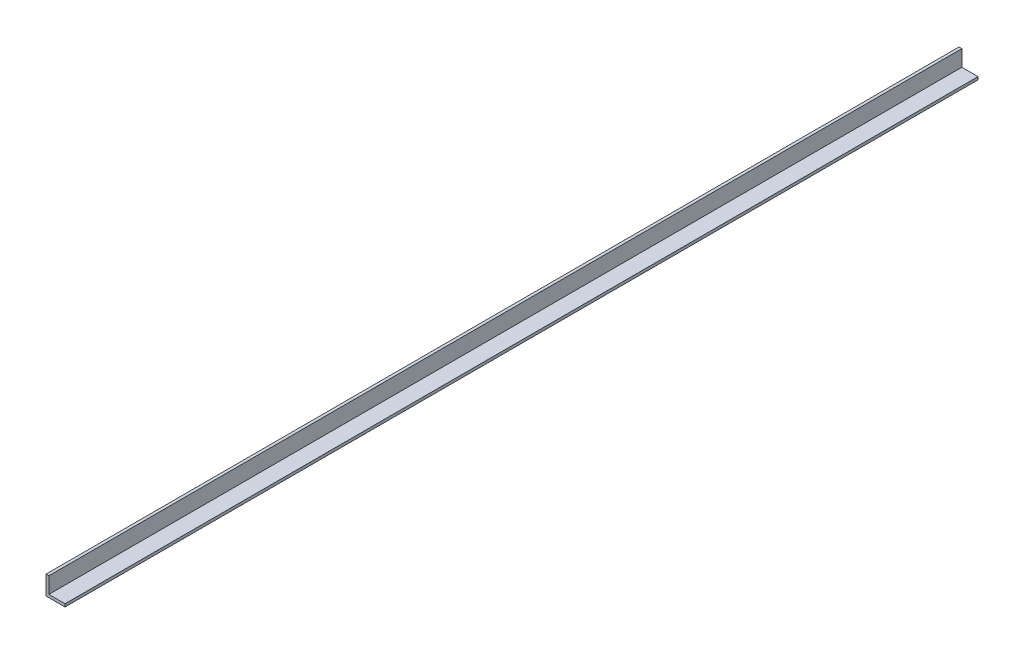
SolidWorks part; units mm, degrees
material "ASTM A36 Acero"
ref_plane "Alzado" through (0, 0, 0) normal (0, 0, 1) x (1, 0, 0)
ref_plane "Planta" through (0, 0, 0) normal (0, 1, 0) x (1, 0, 0)
ref_plane "Vista lateral" through (0, 0, 0) normal (1, 0, 0) x (0, 0, -1)
sketch "Croquis1" plane through (0, 0, 0) normal (0, 0, 1) x (1, 0, 0)
  line L0 (0, 127) -> (0, 0)
  line L1 (0, 0) -> (127, 0)
  line L2 (127, 0) -> (127, 19.05)
  line L3 (127, 19.05) -> (19.05, 19.05)
  line L4 (19.05, 19.05) -> (19.05, 127)
  line L5 (19.05, 127) -> (0, 127)
  dimension "D1" = 19.05
  dimension "D2" = 127
extrude "Saliente-Extruir1" add sketch "Croquis1" against normal blind 6100
